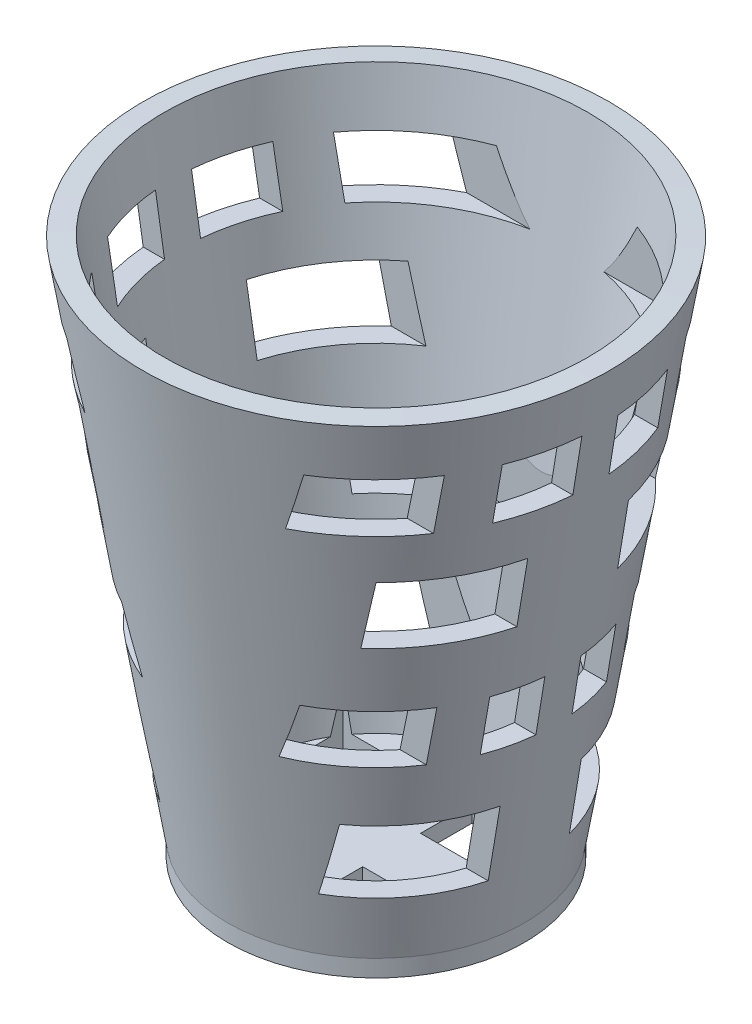
SolidWorks part; units mm, degrees
ref_plane "Front Plane" through (0, 0, 0) normal (0, 0, 1) x (1, 0, 0)
ref_plane "Top Plane" through (0, 0, 0) normal (0, 1, 0) x (1, 0, 0)
ref_plane "Right Plane" through (0, 0, 0) normal (1, 0, 0) x (0, 0, -1)
sketch "Sketch1" plane through (0, 0, 0) normal (0, 0, 1) x (1, 0, 0)
  line L0 (0, 0) -> (0, 61.5055) construction
  line L1 (25, 61.5055) -> (15, 0)
  line L3 (27.4773, 61.3657) -> (17.5, 0)
  line L4 (17.5, 0) -> (15, 0)
  line L5 (25, 61.5055) -> (27.4773, 61.3657)
  line L6 (17.5, 0) -> (0, 0)
  line L7 (17.5, 0) -> (17.5, -2)
  line L8 (17.5, -2) -> (0, -2)
  line L9 (0, 0) -> (0, -2)
  point P7 (22.4886, 30.6828)
  dimension "D1" = 15
  dimension "D2" = 2.5
  dimension "D3" = 25
  dimension "D4" = 2
revolve "Revolve1" add sketch "Sketch1" angle 360 about L0
sketch "Sketch2" plane through (0, 0, 0) normal (1, 0, 0) x (0, 0, -1)
  line L0 (0, 61.5055) -> (0, -2) construction
  line L1 (25, 61.5055) -> (-25, 61.5055) construction
  line L2 (-17.5, -2) -> (17.5, -2) construction
  line L3 (2.1255, 28.4686) -> (2.1255, 22.0035)
  line L4 (-22.4949, 55.2145) -> (-14.2586, 55.2145)
  line L5 (-22.4949, 55.2145) -> (-22.4949, 48.6609)
  line L6 (-22.4949, 48.6609) -> (-14.2586, 48.6609)
  line L7 (-14.2586, 55.2145) -> (-14.2586, 48.6609)
  line L8 (-9.7419, 55.2145) -> (-2.1255, 55.2145)
  line L9 (-9.7419, 55.2145) -> (-9.7419, 48.6609)
  line L10 (-9.7419, 48.6609) -> (-2.1255, 48.6609)
  line L11 (-2.1255, 55.2145) -> (-2.1255, 48.6609)
  line L12 (-17.3583, 43.3471) -> (-5.9337, 43.3471)
  line L13 (-17.3583, 43.3471) -> (-17.3583, 35.7307)
  line L14 (-17.3583, 35.7307) -> (-5.9337, 35.7307)
  line L15 (-5.9337, 43.3471) -> (-5.9337, 35.7307)
  line L16 (-19.4838, 28.4686) -> (-11.646, 28.4686)
  line L17 (-19.4838, 28.4686) -> (-19.4838, 22.0035)
  line L18 (-19.4838, 22.0035) -> (-11.646, 22.0035)
  line L19 (-11.646, 28.4686) -> (-11.646, 22.0035)
  line L20 (-7.4393, 28.4686) -> (-2.1255, 28.4686)
  line L21 (-7.4393, 28.4686) -> (-7.4393, 22.0035)
  line L22 (-7.4393, 22.0035) -> (-2.1255, 22.0035)
  line L23 (-2.1255, 28.4686) -> (-2.1255, 22.0035)
  line L24 (-16.1184, 15.2727) -> (-4.7824, 15.2727)
  line L25 (-16.1184, 15.2727) -> (-16.1184, 6.9478)
  line L26 (-16.1184, 6.9478) -> (-4.7824, 6.9478)
  line L27 (-4.7824, 15.2727) -> (-4.7824, 6.9478)
  line L28 (2.1255, 55.2145) -> (2.1255, 48.6609)
  line L29 (4.7824, 15.2727) -> (4.7824, 6.9478)
  line L30 (16.1184, 6.9478) -> (4.7824, 6.9478)
  line L31 (16.1184, 15.2727) -> (16.1184, 6.9478)
  line L32 (16.1184, 15.2727) -> (4.7824, 15.2727)
  line L33 (7.4393, 22.0035) -> (2.1255, 22.0035)
  line L34 (7.4393, 28.4686) -> (7.4393, 22.0035)
  line L35 (7.4393, 28.4686) -> (2.1255, 28.4686)
  line L36 (11.646, 28.4686) -> (11.646, 22.0035)
  line L37 (19.4838, 22.0035) -> (11.646, 22.0035)
  line L38 (19.4838, 28.4686) -> (19.4838, 22.0035)
  line L39 (19.4838, 28.4686) -> (11.646, 28.4686)
  line L40 (5.9337, 43.3471) -> (5.9337, 35.7307)
  line L41 (17.3583, 35.7307) -> (5.9337, 35.7307)
  line L42 (17.3583, 43.3471) -> (17.3583, 35.7307)
  line L43 (17.3583, 43.3471) -> (5.9337, 43.3471)
  line L44 (9.7419, 48.6609) -> (2.1255, 48.6609)
  line L45 (9.7419, 55.2145) -> (9.7419, 48.6609)
  line L46 (9.7419, 55.2145) -> (2.1255, 55.2145)
  line L47 (14.2586, 55.2145) -> (14.2586, 48.6609)
  line L48 (22.4949, 48.6609) -> (14.2586, 48.6609)
  line L49 (22.4949, 55.2145) -> (22.4949, 48.6609)
  line L50 (22.4949, 55.2145) -> (14.2586, 55.2145)
extrude "Cut-Extrude1" cut sketch "Sketch2" against normal mid plane 75
sketch "Sketch3" plane through (0, -2, 0) normal (0, -1, 0) x (1, 0, 0)
  line L1 (10.8059, -9.0816) -> (2.2225, -9.0816)
  line L2 (10.8059, -9.0816) -> (10.8059, -3.0272)
  line L3 (10.8059, -3.0272) -> (2.2225, -3.0272)
  line L4 (2.2225, -9.0816) -> (2.2225, -3.0272)
  line L5 (-5.5179, -9.0816) -> (-12.9518, -9.0816)
  line L6 (-5.5179, -9.0816) -> (-5.5179, -3.0272)
  line L7 (-5.5179, -3.0272) -> (-12.9518, -3.0272)
  line L8 (-12.9518, -9.0816) -> (-12.9518, -3.0272)
  line L9 (10.8059, 3.7936) -> (2.2225, 3.7936)
  line L10 (10.8059, 3.7936) -> (10.8059, 9.2349)
  line L11 (10.8059, 9.2349) -> (2.2225, 9.2349)
  line L12 (2.2225, 3.7936) -> (2.2225, 9.2349)
  line L13 (-5.5179, 4.33) -> (-12.9518, 4.33)
  line L14 (-5.5179, 4.33) -> (-5.5179, 9.2349)
  line L15 (-5.5179, 9.2349) -> (-12.9518, 9.2349)
  line L16 (-12.9518, 4.33) -> (-12.9518, 9.2349)
extrude "Cut-Extrude2" cut sketch "Sketch3" against normal blind 5 contours L2 L1 L4 L3 | L6 L5 L8 L7 | L10 L9 L12 L11 | L14 L13 L16 L15
